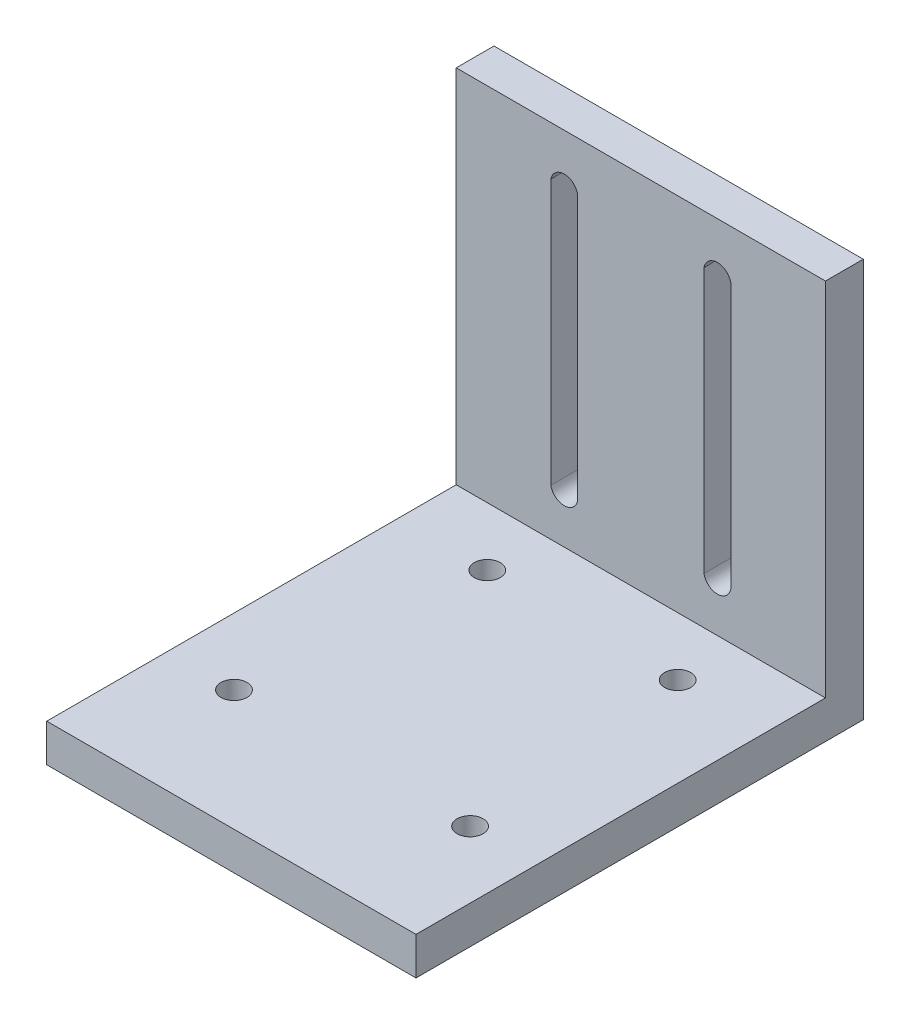
SolidWorks part; units mm, degrees
ref_plane "Front Plane" through (0, 0, 0) normal (0, 0, 1) x (1, 0, 0)
ref_plane "Top Plane" through (0, 0, 0) normal (0, 1, 0) x (1, 0, 0)
ref_plane "Right Plane" through (0, 0, 0) normal (1, 0, 0) x (0, 0, -1)
ref_plane "Plane1" through (-15.2622, 0, 0) normal (-1, 0, 0) x (0, -1, 0)
sketch "Sketch1" plane through (-15.2622, 0, 0) normal (-1, 0, 0) x (0, -1, 0)
  line L0 (53.3716, 76.327) -> (-14.7004, 76.327)
  line L1 (-14.7004, 76.327) -> (-14.7004, 0)
  line L2 (-14.7004, 0) -> (53.3716, 0)
  line L3 (53.3716, 0) -> (53.3716, 76.327)
extrude "Boss-Extrude1" add sketch "Sketch1" against normal blind 63.0174
sketch "Sketch2" plane through (47.7552, 0, 0) normal (1, 0, 0) x (0, 0, -1)
  line L0 (-6.4516, -46.92) -> (-6.4516, 14.7004)
  line L1 (-6.4516, 14.7004) -> (-76.327, 14.7004)
  line L2 (-76.327, 14.7004) -> (-76.327, -46.92)
  line L3 (-76.327, -46.92) -> (-6.4516, -46.92)
extrude "Cut-Extrude1" cut sketch "Sketch2" against normal through all
sketch "Sketch3" plane through (0, 0, 6.4516) normal (0, 0, 1) x (1, 0, 0)
  line L0 (5.4642, -38.8931) -> (5.4642, 6.3179)
  line L1 (0.8922, 6.3409) -> (0.8922, -38.9162)
  arc A0 (5.4642, 6.3179) -> (0.8922, 6.3409) centre (3.176, 5.8968) ccw
  arc A1 (0.8922, -38.9162) -> (5.4642, -38.8931) centre (3.176, -38.472) ccw
extrude "Cut-Extrude2" cut sketch "Sketch3" against normal through all
sketch "Sketch4" plane through (0, 0, 0) normal (0, 0, -1) x (-1, 0, 0)
  line L0 (-27.0288, -38.8931) -> (-27.0288, 6.3179)
  line L1 (-31.6008, 6.3409) -> (-31.6008, -38.9162)
  arc A0 (-31.6008, -38.9162) -> (-27.0288, -38.8931) centre (-29.317, -38.472) ccw
  arc A1 (-27.0288, 6.3179) -> (-31.6008, 6.3409) centre (-29.317, 5.8968) ccw
extrude "Cut-Extrude3" cut sketch "Sketch4" against normal through all
hole_wizard "M4 Clearance Hole1" positions "Sketch6" profile "Sketch5" hole size "M4" standard "Ansi Metric"
sketch "Sketch6" plane through (0, -53.3716, 0) normal (0, -1, 0) x (1, 0, 0)
  point P0 (32.4931, 16.4089)
  point P1 (0, 16.4089)
  point P2 (36.392, 55.7351)
  point P3 (-3.8989, 55.7351)
sketch "Sketch5" plane through (32.4931, -53.3716, 16.4089) normal (1, 0, 0) x (0, 0, -1)
  line L0 (0, 0) -> (0, 68.072)
  line L1 (0, 68.072) -> (2.2225, 68.072)
  line L2 (2.2225, 68.072) -> (2.2225, 0)
  line L5 (2.2225, 0) -> (0, 0)
  line L11 (0, -6.35) -> (0, 107.95) construction
  dimension "Thru Hole Dia." = 4.445
  dimension "Thru Hole Depth" = 68.072
